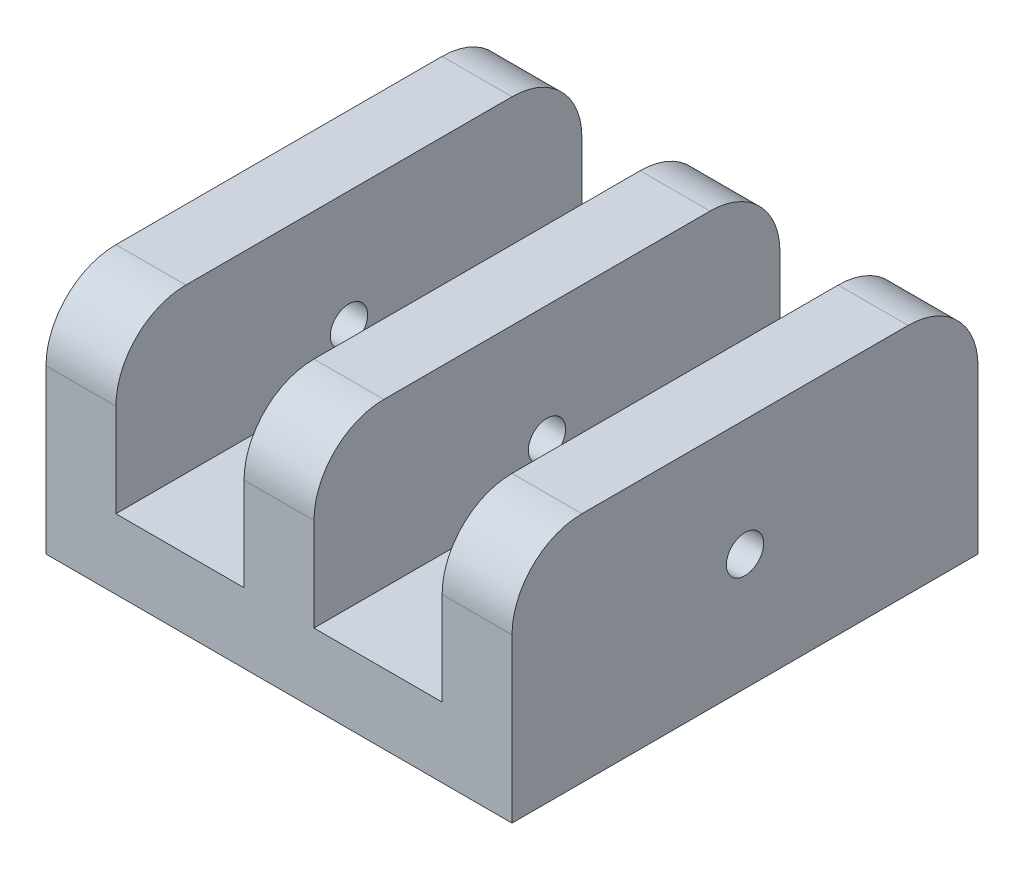
SolidWorks part; units mm, degrees
ref_plane "Front" through (0, 0, 0) normal (0, 0, 1) x (1, 0, 0)
ref_plane "Top" through (0, 0, 0) normal (0, 1, 0) x (1, 0, 0)
ref_plane "Right" through (0, 0, 0) normal (1, 0, 0) x (0, 0, -1)
sketch "Sketch1" plane through (0, 0, 0) normal (0, 0, 1) x (1, 0, 0)
  line L0 (0, 0) -> (50.8, 0)
  line L1 (50.8, 0) -> (50.8, 25.4)
  line L2 (50.8, 25.4) -> (43.18, 25.4)
  line L3 (43.18, 25.4) -> (43.18, 7.62)
  line L4 (43.18, 7.62) -> (29.21, 7.62)
  line L5 (29.21, 7.62) -> (29.21, 25.4)
  line L6 (29.21, 25.4) -> (21.59, 25.4)
  line L7 (21.59, 25.4) -> (21.59, 7.62)
  line L8 (21.59, 7.62) -> (7.62, 7.62)
  line L9 (7.62, 7.62) -> (7.62, 25.4)
  line L10 (7.62, 25.4) -> (0, 25.4)
  line L11 (0, 25.4) -> (0, 0)
  dimension "D1" = 50.8
  dimension "D2" = 7.62
  dimension "D3" = 7.62
  dimension "D4" = 7.62
  dimension "D5" = 13.97
  dimension "D6" = 25.4
  dimension "D7" = 25.4
  dimension "D8" = 17.78
  dimension "D9" = 17.78
  dimension "D10" = 17.78
sketch3d "3DSketch1"
  line L0 (0, 25.4, 0) -> (0, 0, 0) construction
  line L1 (0, 0, 0) -> (50.8, 0, 0) construction
  line L2 (21.59, 7.62, 0) -> (7.62, 7.62, 0) construction
  line L3 (7.62, 25.4, 0) -> (0, 25.4, 0) construction
  line L4 (7.62, 7.62, 0) -> (7.62, 25.4, 0) construction
  line L5 (21.59, 25.4, 0) -> (21.59, 7.62, 0) construction
  line L6 (29.21, 25.4, 0) -> (21.59, 25.4, 0) construction
  line L7 (29.21, 7.62, 0) -> (29.21, 25.4, 0) construction
  line L8 (43.18, 7.62, 0) -> (29.21, 7.62, 0) construction
  line L9 (43.18, 25.4, 0) -> (43.18, 7.62, 0) construction
  line L10 (50.8, 25.4, 0) -> (43.18, 25.4, 0) construction
  line L11 (50.8, 0, 0) -> (50.8, 25.4, 0) construction
  line L12 (0, 25.4, 0) -> (0, 0, 0)
  line L13 (0, 0, 0) -> (50.8, 0, 0)
  line L14 (21.59, 7.62, 0) -> (7.62, 7.62, 0)
  line L15 (7.62, 25.4, 0) -> (0, 25.4, 0)
  line L16 (7.62, 7.62, 0) -> (7.62, 25.4, 0)
  line L17 (21.59, 25.4, 0) -> (21.59, 7.62, 0)
  line L18 (29.21, 25.4, 0) -> (21.59, 25.4, 0)
  line L19 (29.21, 7.62, 0) -> (29.21, 25.4, 0)
  line L20 (43.18, 7.62, 0) -> (29.21, 7.62, 0)
  line L21 (43.18, 25.4, 0) -> (43.18, 7.62, 0)
  line L22 (50.8, 25.4, 0) -> (43.18, 25.4, 0)
  line L23 (50.8, 0, 0) -> (50.8, 25.4, 0)
extrude "Boss-Extrude1" add sketch "3DSketch1" along direction (0, 0, 1) on the side against the normal blind 50.8
fillet "Fillet3" radius 7.62 3 edges
fillet "Fillet4" radius 7.62 3 edges
sketch "Sketch3" plane through (0, 7.62, 0) normal (0, 1, 0) x (1, 0, 0)
  line L0 (21.59, -7.62) -> (21.59, -43.18) construction
  line L2 (43.18, -7.62) -> (43.18, -43.18) construction
  line L3 (0, 0) -> (50.8, 0) construction
  line L5 (21.59, -50.8) -> (7.62, -50.8) construction
  circle A0 centre (14.605, -25.4) radius 0.5334
  circle A1 centre (36.195, -25.4) radius 0.5334
  dimension "D1" = 1.0668
  dimension "D2" = 1.0668
  dimension "D3" = 6.985
  dimension "D4" = 6.985
  dimension "D5" = 25.4
  dimension "D6" = 25.4
extrude "Cut-Extrude1" cut sketch "Sketch3" against normal through all
sketch "Sketch4" plane through (50.8, 0, 0) normal (1, 0, 0) x (0, 0, -1)
  line L0 (0, 0) -> (-50.8, 0) construction
  line L3 (-50.8, 0) -> (-50.8, 17.78) construction
  circle A0 centre (-25.4, 12.7) radius 2.032
  dimension "D1" = 4.064
  dimension "D2" = 12.7
  dimension "D3" = 25.4
extrude "Cut-Extrude2" cut sketch "Sketch4" against normal through all
sketch "Sketch6" plane through (50.8, 0, 0) normal (1, 0, 0) x (0, 0, -1)
